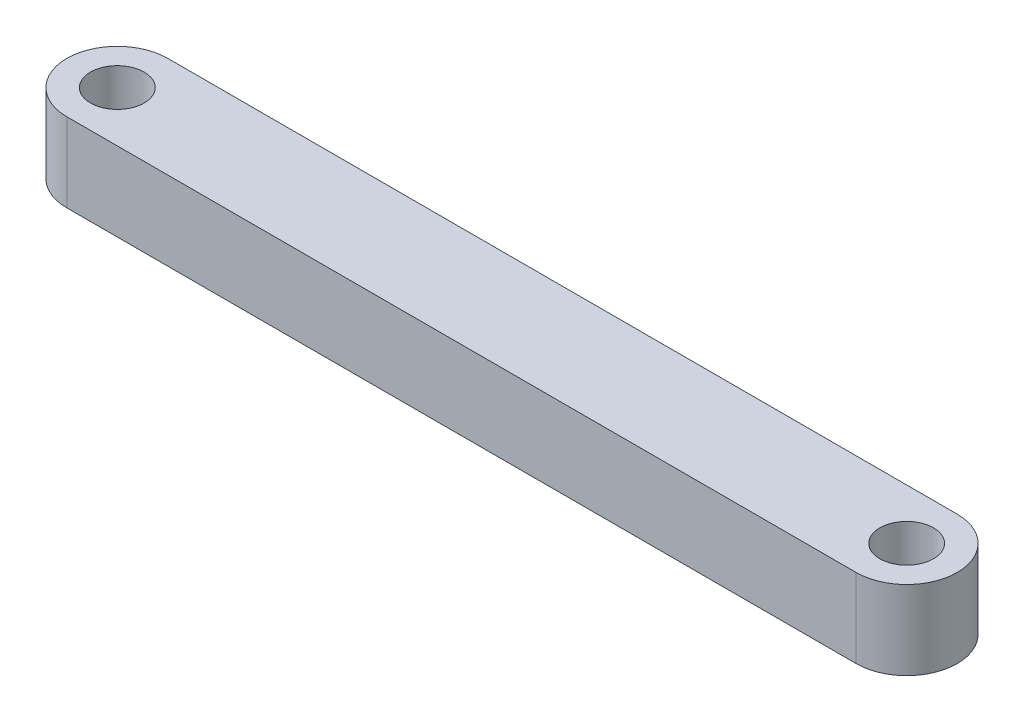
SolidWorks part; units mm, degrees
material "PET"
ref_plane "Front Plane" through (0, 0, 0) normal (0, 0, 1) x (1, 0, 0)
ref_plane "Top Plane" through (0, 0, 0) normal (0, 1, 0) x (1, 0, 0)
ref_plane "Right Plane" through (0, 0, 0) normal (1, 0, 0) x (0, 0, -1)
sketch "Sketch1" plane through (0, 0, 0) normal (0, 1, 0) x (1, 0, 0)
  line L0 (0, 0) -> (63.5, 0) construction
  line L1 (0, 4.064) -> (63.5, 4.064)
  line L2 (0, -4.064) -> (63.5, -4.064)
  line L3 (31.75, -4.064) -> (31.75, 4.064) construction
  arc A0 (0, 4.064) -> (0, -4.064) centre (0, 0) ccw
  arc A1 (63.5, -4.064) -> (63.5, 4.064) centre (63.5, 0) ccw
  circle A2 centre (0, 0) radius 2.159
  circle A3 centre (63.5, 0) radius 2.159
  point P3 (31.75, 0)
  point P13 (31.75, 0)
  dimension "D2" = 4.318
  dimension "D3" = 1.905
  dimension "D1" = 63.5
extrude "Boss-Extrude1" add sketch "Sketch1" along normal blind 6.35 contours L1 A1 L2 A0
